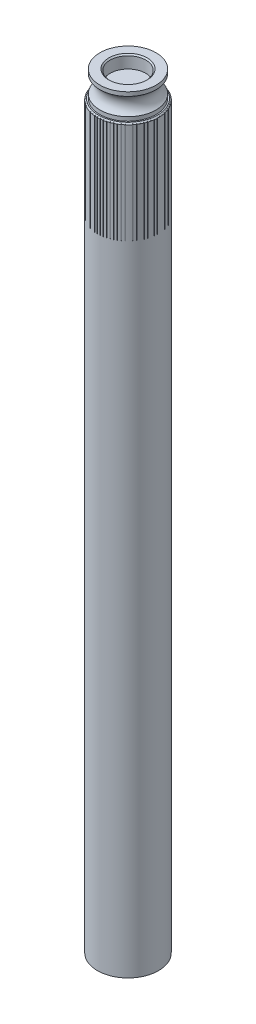
SolidWorks part; units mm, degrees
ref_plane "Front Plane" through (0, 0, 0) normal (0, 0, 1) x (1, 0, 0)
ref_plane "Top Plane" through (0, 0, 0) normal (0, 1, 0) x (1, 0, 0)
ref_plane "Right Plane" through (0, 0, 0) normal (1, 0, 0) x (0, 0, -1)
sketch "Sketch1" plane through (0, 0, 0) normal (0, 0, 1) x (1, 0, 0)
  line L0 (0, 0) -> (0, 300)
  line L5 (0, 300) -> (-11, 300)
  line L6 (-11, 300) -> (-11, 290)
  line L7 (-11, 290) -> (-12, 290)
  line L8 (-12, 290) -> (-12, 0)
  line L9 (-12, 0) -> (0, 0)
  dimension "D1" = 300
  dimension "D2" = 10
  dimension "D3" = 12
  dimension "D4" = 11
revolve "Revolve1" add sketch "Sketch1" angle 360 about L0
sketch "Sketch2" plane through (0, 0, 0) normal (0, 0, 1) x (1, 0, 0)
  line L0 (0, 0) -> (0, 300) construction
  line L2 (12, 290) -> (-12, 290) construction
  line L3 (-13.5, 295) -> (-11, 295) construction
  line L4 (-11, 300) -> (-11, 290) construction
  line L5 (11, 300) -> (-11, 300) construction
  line L6 (-11, 300) -> (-11, 290) construction
  circle A0 centre (-13.5, 295) radius 4.25
  dimension "D2" = 8.5
  dimension "D1" = 2.5
revolve "Cut-Revolve1" cut sketch "Sketch2" angle 360 about L0
sketch "Sketch3" plane through (0, 300, 0) normal (0, 1, 0) x (1, 0, 0)
  circle A3 centre (0, 0) radius 7
  circle A4 centre (0, 0) radius 7
  dimension "D1" = 4
extrude "Cut-Extrude1" cut sketch "Sketch3" against normal blind 5
chamfer "Chamfer1" distance 0.5 angle 45 2 edges at (0, 290, -12) (0, 300, 7)
sketch "Sketch4" plane through (0, 290, 0) normal (0, 1, 0) x (1, 0, 0)
  line L1 (-0.05, 11.8) -> (0.05, 11.8)
  line L2 (-0.05, 11.8) -> (-0.05, 12.2)
  line L3 (-0.05, 12.2) -> (0.05, 12.2)
  line L4 (0.05, 11.8) -> (0.05, 12.2)
  line L5 (-0.05, 11.8) -> (0.05, 12.2) construction
  line L6 (-0.05, 12.2) -> (0.05, 11.8) construction
  circle A0 centre (0, 0) radius 12 construction
  circle A1 centre (0, 0) radius 12 construction
  point P0 (0, 12)
  dimension "D1" = 0.1
  dimension "D2" = 0.4
extrude "Cut-Extrude2" cut sketch "Sketch4" against normal blind 40
pattern_circular "CirPattern1" count 70 over 360 about axis through (0, 0, 0) along (0, 1, 0) of "Cut-Extrude2"
